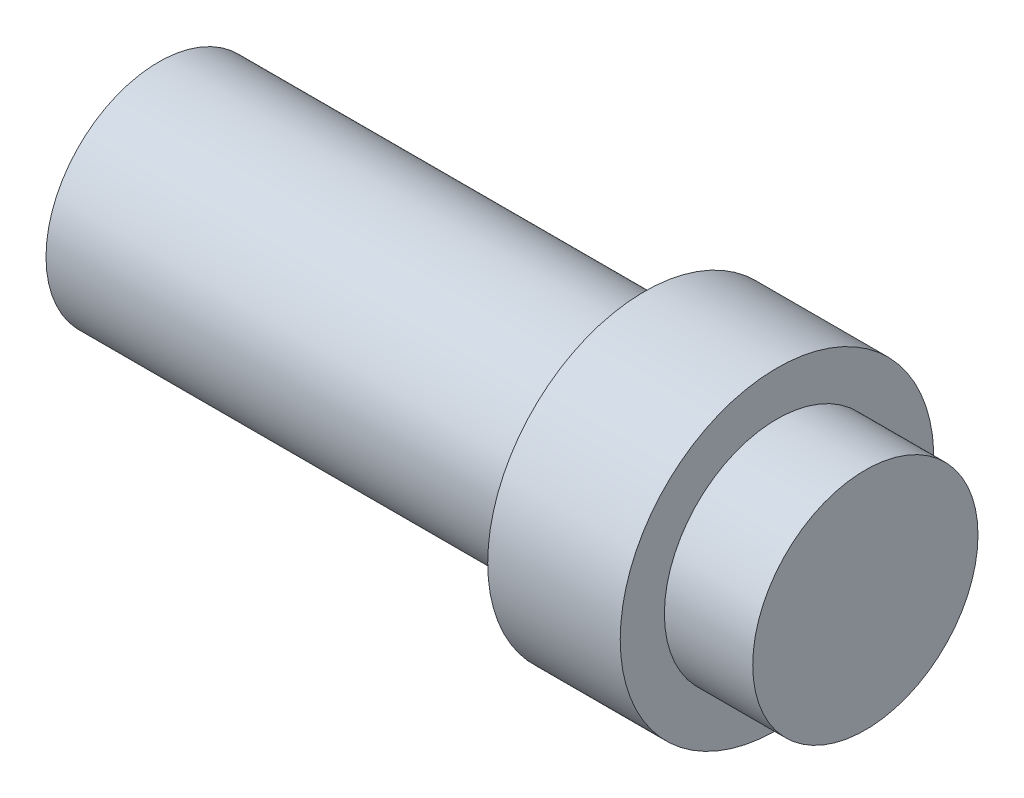
SolidWorks part; units mm, degrees
ref_plane "前视基准面" through (0, 0, 0) normal (0, 0, 1) x (1, 0, 0)
ref_plane "上视基准面" through (0, 0, 0) normal (0, 1, 0) x (1, 0, 0)
ref_plane "右视基准面" through (0, 0, 0) normal (1, 0, 0) x (0, 0, -1)
sketch "草图1" plane through (0, 0, 0) normal (0, 0, 1) x (1, 0, 0)
  line L0 (-84.796, 0) -> (66.6524, 0) construction
  line L1 (-25, 0) -> (-25, 5.1)
  line L2 (0, 69.6763) -> (0, -59.0926) construction
  line L3 (-25, 5.1) -> (-3, 5.1)
  line L4 (-3, 5.1) -> (-3, 7.1)
  line L5 (-3, 7.1) -> (3, 7.1)
  line L6 (3, 7.1) -> (3, 5.1)
  line L7 (3, 5.1) -> (7, 5.1)
  line L8 (7, 5.1) -> (7, 0)
  line L9 (7, 0) -> (-25, 0)
  dimension "D1" = 6
  dimension "D2" = 22
  dimension "D3" = 4
  dimension "D4" = 5.1
  dimension "D5" = 2
revolve "旋转1" add sketch "草图1" angle 360 about L0
